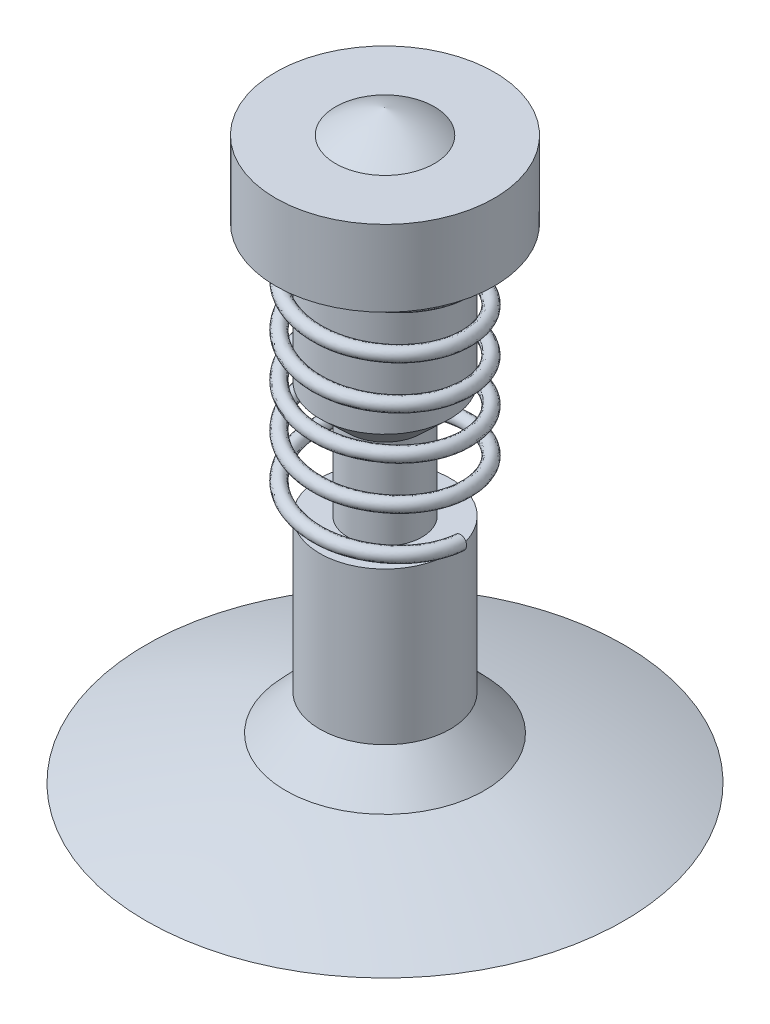
SolidWorks part; units mm, degrees
ref_plane "Front Plane" through (0, 0, 0) normal (0, 0, 1) x (1, 0, 0)
ref_plane "Top Plane" through (0, 0, 0) normal (0, 1, 0) x (1, 0, 0)
ref_plane "Right Plane" through (0, 0, 0) normal (1, 0, 0) x (0, 0, -1)
sketch "Sketch1" plane through (0, 0, 0) normal (0, 0, 1) x (1, 0, 0)
  line L0 (0, 2.69) -> (0, 0)
  line L1 (0, 0) -> (1.1, 0)
  line L2 (0.4573, 0.1976) -> (0.3, 0.3638)
  line L3 (0.3, 0.3638) -> (0.3, 1.0639)
  line L4 (0.3, 1.0639) -> (0.17, 1.0639)
  line L5 (0.17, 1.0639) -> (0.17, 1.4779)
  line L6 (0.17, 1.4779) -> (0.3, 1.6009)
  line L7 (0.3, 1.6009) -> (0.3, 2.2309)
  line L8 (0.3, 2.2309) -> (0.503, 2.2309)
  line L9 (0.503, 2.2309) -> (0.503, 2.5809)
  line L10 (0.503, 2.5809) -> (0.2271, 2.5809)
  arc A0 (1.1, 0) -> (0.4573, 0.1976) centre (-0.5626, -4.2635) ccw
  arc A2 (0.2271, 2.5809) -> (0, 2.69) centre (-0.1849, 2.0142) ccw
  point P16 (0.2486, 0.3595)
  point P17 (-0.0305, 0.8427)
  point P18 (0.1019, 0.4633)
  point P19 (0.4912, 2.5651)
  point P20 (0.0817, 2.2934)
  point P21 (0.3054, 1.9139)
  point P22 (0.2605, 0.4226)
  point P23 (0.1652, 1.2988)
  point P24 (0.2882, 1.82)
  point P25 (0, 0)
  point P26 (0.2271, 2.5809)
  point P27 (0.367, 0.2173)
  point P28 (0.3, 0.3638)
  dimension "D1" = 2.69
  dimension "D2" = 1.1
  dimension "D3" = 0.35
  dimension "D4" = 0.63
  dimension "D5" = 0.17
  dimension "D6" = 0.3
  dimension "D7" = 0.3
revolve "Revolve1" add sketch "Sketch1" angle 360 about L0
sketch "Sketch2" plane through (0, 2.2309, 0) normal (0, -1, 0) x (1, 0, 0)
  circle A0 centre (0, 0) radius 0.345
  dimension "D1" = 0.69
curve "Helix/Spiral1" pitch 0.2 height 1.1 turns 5.5
sweep "Sweep1" add path "Helix/Spiral1" circular profile diameter 0.06 parameters "D3"=0.06
